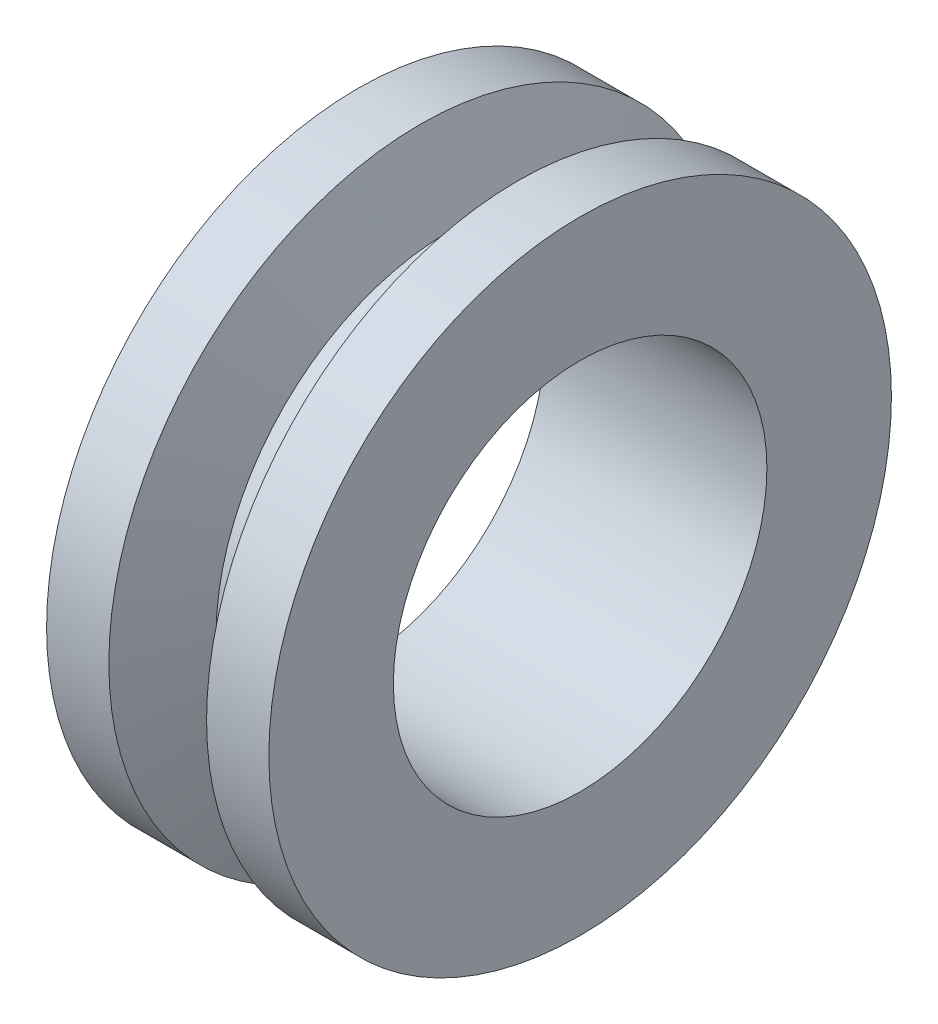
SolidWorks part; units mm, degrees
ref_plane "Front Plane" through (0, 0, 0) normal (0, 0, 1) x (1, 0, 0)
ref_plane "Top Plane" through (0, 0, 0) normal (0, 1, 0) x (1, 0, 0)
ref_plane "Right Plane" through (0, 0, 0) normal (1, 0, 0) x (0, 0, -1)
sketch "Sketch2" plane through (0, 0, 0) normal (0, 0, 1) x (1, 0, 0)
  line L0 (0, 0) -> (-54.5285, 0) construction
  line L1 (27.1637, 24) -> (-1.3969, 24)
  line L2 (-1.3969, 24) -> (-1.3969, 40)
  line L3 (-1.3969, 40) -> (6.6031, 40)
  line L4 (6.6031, 40) -> (10.3834, 30)
  line L5 (10.3834, 30) -> (15.3834, 30)
  line L6 (15.3834, 30) -> (19.1637, 40)
  line L7 (19.1637, 40) -> (27.1637, 40)
  line L8 (27.1637, 40) -> (27.1637, 24)
  dimension "D1" = 24
  dimension "D2" = 5
  dimension "D3" = 8
  dimension "D4" = 10
  dimension "D5" = 80
revolve "Revolve1" add sketch "Sketch2" angle 360 about L0
